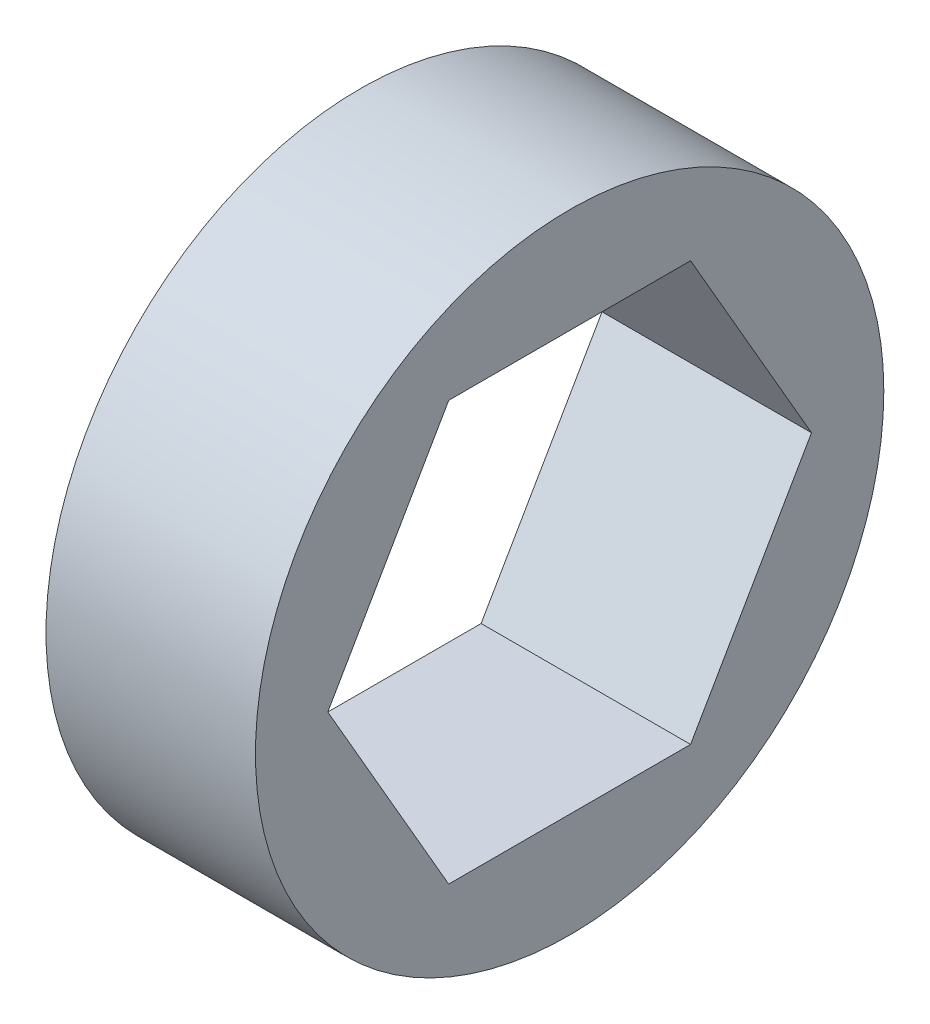
SolidWorks part; units mm, degrees
material "6063-T5"
ref_plane "Front" through (0, 0, 0) normal (0, 0, 1) x (1, 0, 0)
ref_plane "Top" through (0, 0, 0) normal (0, 1, 0) x (1, 0, 0)
ref_plane "Right" through (0, 0, 0) normal (1, 0, 0) x (0, 0, -1)
sketch "Sketch1" plane through (0, 0, 0) normal (1, 0, 0) x (0, 0, -1)
  line L1 (3.6662, 6.35) -> (-3.6662, 6.35)
  line L2 (-3.6662, 6.35) -> (-7.3323, 0)
  line L3 (-7.3323, 0) -> (-3.6662, -6.35)
  line L4 (-3.6662, -6.35) -> (3.6662, -6.35)
  line L5 (3.6662, -6.35) -> (7.3323, 0)
  line L6 (7.3323, 0) -> (3.6662, 6.35)
  circle A0 centre (0, 0) radius 9.525
  circle A1 centre (0, 0) radius 6.35 construction
  dimension "D2" = 19.05
  dimension "D1" = 12.7
extrude "Boss-Extrude1" add sketch "Sketch1" along normal blind 6.35
